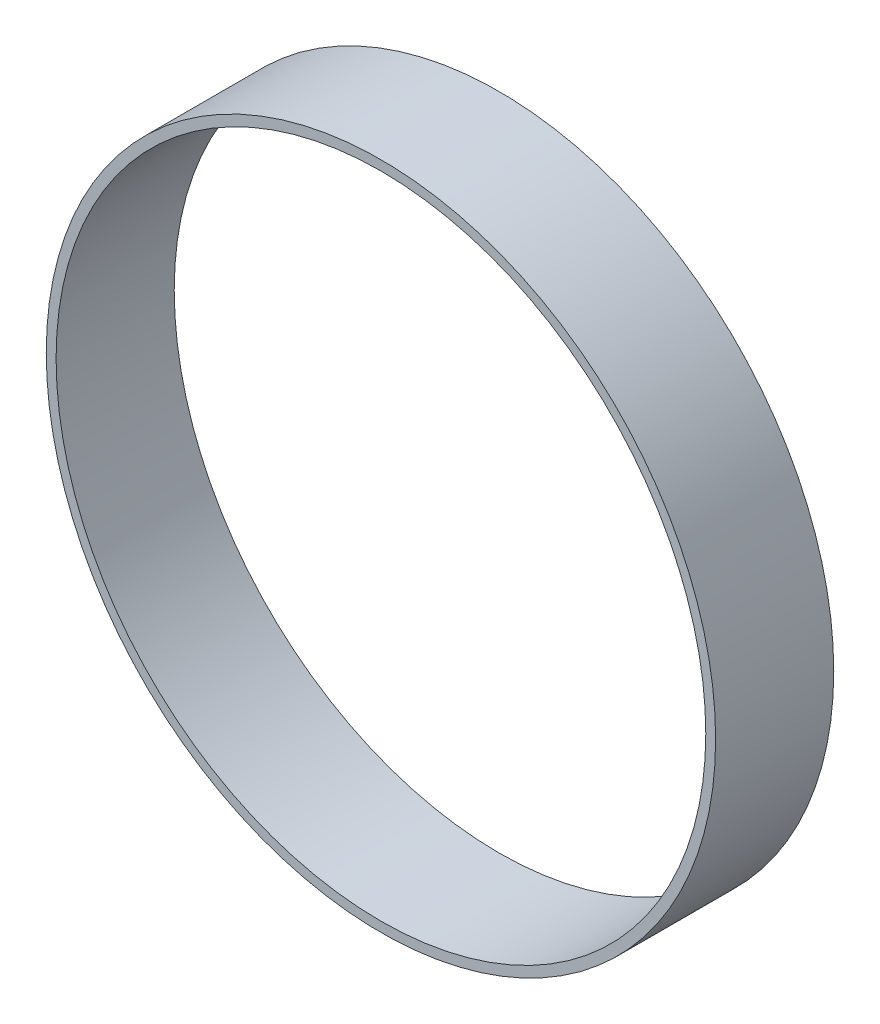
SolidWorks part; units mm, degrees
ref_plane "Front Plane" through (0, 0, 0) normal (1, 0, 0) x (0, 1, 0)
ref_plane "Top Plane" through (0, 0, 0) normal (0, 0, 1) x (0, 1, 0)
ref_plane "Right Plane" through (0, 0, 0) normal (0, 1, 0) x (-1, 0, 0)
sketch "Sketch1" plane through (0, 0, 0) normal (0, 0, 1) x (0, 1, 0)
  circle A0 centre (0, 0) radius 107.95
  circle A1 centre (0, 0) radius 104.775
  dimension "D1" = 209.55
  dimension "D2" = 3.175
extrude "Boss-Extrude1" add sketch "Sketch1" along normal blind 38.1
